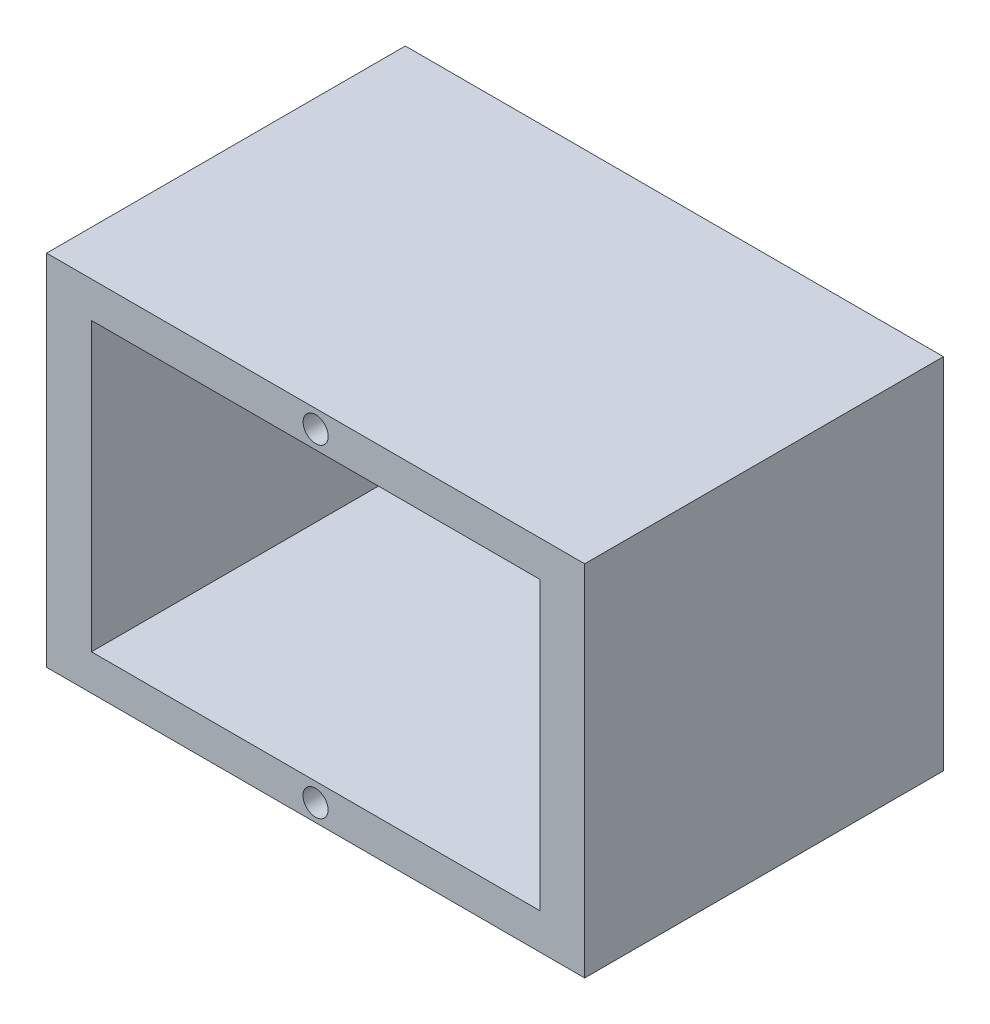
SolidWorks part; units mm, degrees
material "ABS PC"
ref_plane "Front Plane" through (0, 0, 0) normal (0, 0, 1) x (1, 0, 0)
ref_plane "Top Plane" through (0, 0, 0) normal (0, 1, 0) x (1, 0, 0)
ref_plane "Right Plane" through (0, 0, 0) normal (1, 0, 0) x (0, 0, -1)
sketch "Sketch9" plane through (0, 0, 0) normal (0, 0, 1) x (1, 0, 0)
  line L1 (-7.4533, 9.3501) -> (68.7467, 9.3501)
  line L2 (-7.4533, 9.3501) -> (-7.4533, -41.4499)
  line L3 (-7.4533, -41.4499) -> (68.7467, -41.4499)
  line L4 (68.7467, 9.3501) -> (68.7467, -41.4499)
  dimension "D1" = 76.2
  dimension "D2" = 50.8
extrude "Boss-Extrude2" add sketch "Sketch9" along normal blind 50.8 contours L1 L4 L3 L2
sketch "Sketch10" plane through (0, 0, 50.8) normal (0, 0, 1) x (1, 0, 0)
  line L0 (-7.4533, -16.0499) -> (68.7467, -16.0499)
  line L1 (-7.4533, 9.3501) -> (-7.4533, -41.4499) construction
  line L2 (68.7467, 9.3501) -> (68.7467, -41.4499) construction
  line L4 (-1.1033, -36.3699) -> (62.3967, -36.3699)
  line L5 (-1.1033, -36.3699) -> (-1.1033, 4.2701)
  line L6 (-1.1033, 4.2701) -> (62.3967, 4.2701)
  line L7 (62.3967, -36.3699) -> (62.3967, 4.2701)
  line L8 (-1.1033, -36.3699) -> (62.3967, 4.2701) construction
  line L9 (-1.1033, 4.2701) -> (62.3967, -36.3699) construction
  point P6 (30.6467, -16.0499)
  dimension "D1" = 40.64
  dimension "D2" = 63.5
extrude "Cut-Extrude3" cut sketch "Sketch10" against normal blind 40.64 contours L0 L7 L6 L5 | L4 L7 L0 L5
sketch "Sketch11" plane through (0, 0, 10.16) normal (0, 0, 1) x (1, 0, 0)
  circle A0 centre (15.5663, -14.5844) radius 1.5875
  circle A1 centre (32.0763, -14.5844) radius 3.175
  dimension "D1" = 3.175
  dimension "D2" = 6.35
  dimension "D3" = 16.51
extrude "Cut-Extrude4" cut sketch "Sketch11" against normal through all
sketch "Sketch12" plane through (0, 0, 50.8) normal (0, 0, 1) x (1, 0, 0)
  circle A0 centre (30.6467, 6.8101) radius 1.778
  dimension "D1" = 3.556
extrude "Cut-Extrude5" cut sketch "Sketch12" against normal blind 12.7
sketch "Sketch17" plane through (0, 0, 50.8) normal (0, 0, 1) x (1, 0, 0)
  circle A0 centre (30.6278, -39.0115) radius 1.778
  dimension "D1" = 3.556
sketch "Sketch19" plane through (0, 0, 50.8) normal (0, 0, 1) x (1, 0, 0)
  circle A0 centre (30.6278, -39.0115) radius 1.778
extrude "Cut-Extrude9" cut sketch "Sketch19" against normal blind 12.7
equation "\"GR\"= 24 / 9"
equation "\"Tout\"=0.125"
equation "\"Dout\"= 0.25"
equation "\"Gsout\"= 1100"
equation "\"Din\"= 0.125"
equation "\"I\"= 1"
equation "\"Gsin\"= \"Gsout\" * \"GR\""
equation "\"P\"= \"Tout\" * \"Gsout\""
equation "\"Tin\"= \"P\" / \"Gsin\""
equation "\"Gin\"= 0.375"
equation "\"Gout\"= 1"
equation "\"alpha\"= 20"
equation "\"Clearence\"= 0.001"
equation "\"Pmax\"= 20"
equation "\"Fr\"= ( ( 2 * \"Tin\" ) / \"Gin\" ) * tan ( \"alpha\" )"
equation "\"t\"= ( \"Fr\" / ( 2 * \"Pmax\" * \"Gin\" ) )"
